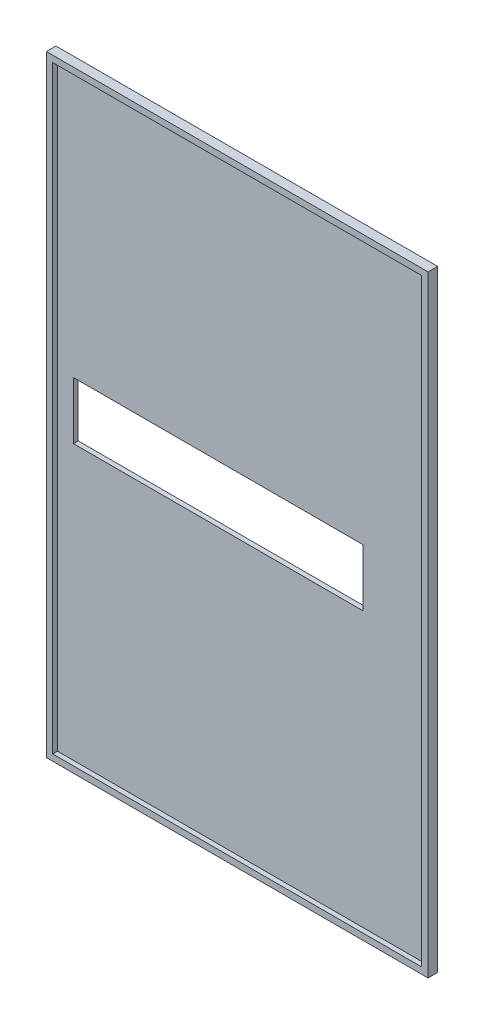
SolidWorks part; units mm, degrees
ref_plane "Front Plane" through (0, 0, 0) normal (0, 0, 1) x (1, 0, 0)
ref_plane "Top Plane" through (0, 0, 0) normal (0, 1, 0) x (1, 0, 0)
ref_plane "Right Plane" through (0, 0, 0) normal (1, 0, 0) x (0, 0, -1)
sketch "Sketch1" plane through (0, 0, 0) normal (0, 0, 1) x (1, 0, 0)
  line L1 (0, 0) -> (120, 0)
  line L2 (0, 0) -> (0, -192.24)
  line L3 (0, -192.24) -> (120, -192.24)
  line L4 (120, 0) -> (120, -192.24)
  dimension "D1" = 120
  dimension "D2" = 192.24
extrude "Boss-Extrude1" add sketch "Sketch1" along normal blind 3
sketch "Sketch2" plane through (0, 0, 3) normal (0, 0, 1) x (1, 0, 0)
  line L0 (120, 0) -> (0, 0) construction
  line L1 (2, -2) -> (118, -2)
  line L2 (2, -2) -> (2, -190.24)
  line L3 (2, -190.24) -> (118, -190.24)
  line L4 (118, -2) -> (118, -190.24)
  line L5 (0, 0) -> (0, -192.24) construction
  line L6 (120, -192.24) -> (120, 0) construction
  line L7 (0, -192.24) -> (120, -192.24) construction
  dimension "D1" = 2
  dimension "D2" = 2
  dimension "D3" = 2
  dimension "D4" = 2
extrude "Cut-Extrude2" cut sketch "Sketch2" against normal blind 1.5
sketch "Sketch3" plane through (0, 0, 0) normal (0, 0, -1) x (-1, 0, 0)
  line L0 (-120, 0) -> (0, 0) construction
  line L1 (-98, -86) -> (-7, -86)
  line L2 (-98, -86) -> (-98, -104)
  line L3 (-98, -104) -> (-7, -104)
  line L4 (-7, -86) -> (-7, -104)
  line L5 (-120, -192.24) -> (-120, 0) construction
  line L6 (0, 0) -> (0, -192.24) construction
  dimension "D1" = 86
  dimension "D2" = 22
  dimension "D3" = 7
  dimension "D4" = 18
extrude "Cut-Extrude3" cut sketch "Sketch3" against normal blind 1.5
